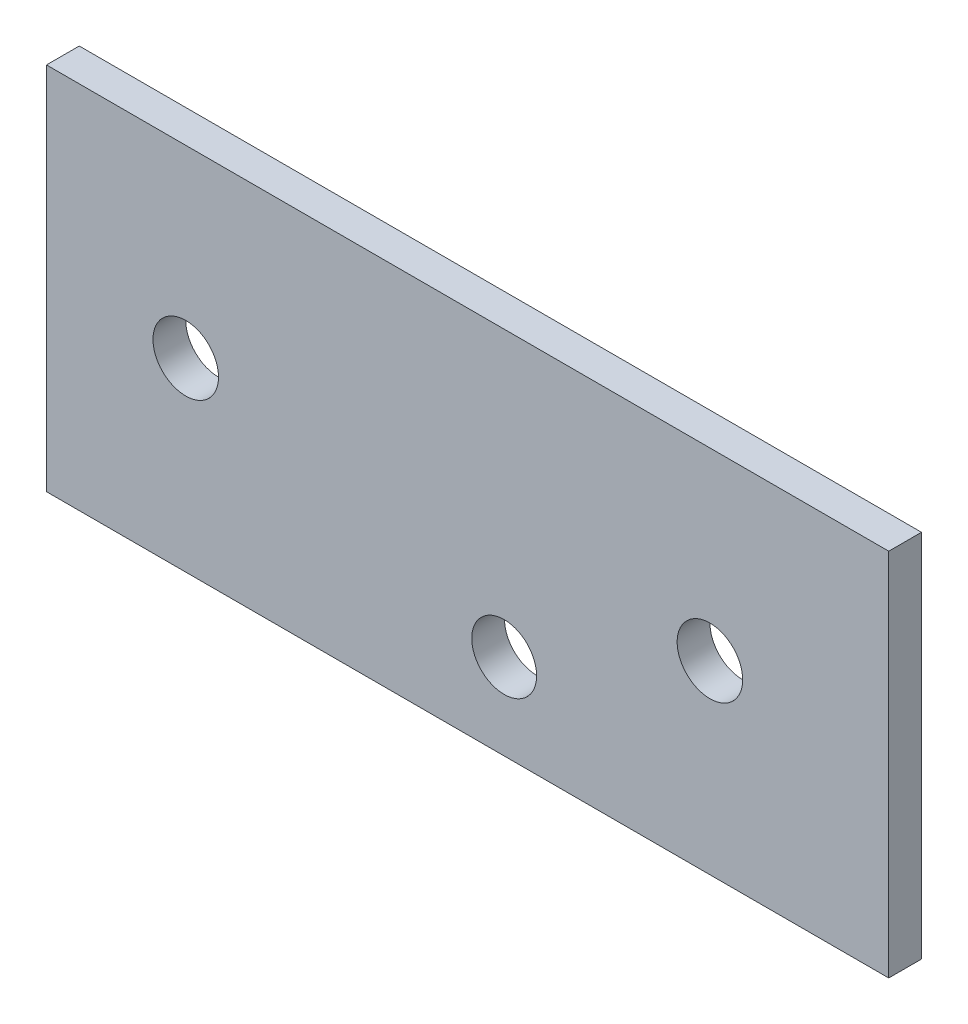
SolidWorks part; units mm, degrees
ref_plane "Front Plane" through (0, 0, 0) normal (0, 0, 1) x (1, 0, 0)
ref_plane "Top Plane" through (0, 0, 0) normal (0, 1, 0) x (1, 0, 0)
ref_plane "Right Plane" through (0, 0, 0) normal (1, 0, 0) x (0, 0, -1)
sketch "Sketch1" plane through (0, 0, 0) normal (0, 0, 1) x (1, 0, 0)
  line L1 (-38.8941, -159.024) -> (42.7306, -159.024)
  line L2 (-38.8941, -159.024) -> (-38.8941, -194.8462)
  line L3 (-38.8941, -194.8462) -> (42.7306, -194.8462)
  line L4 (42.7306, -159.024) -> (42.7306, -194.8462)
  circle A0 centre (-25.4, -176.8929) radius 3.175
  circle A1 centre (25.4, -176.8929) radius 3.175
  circle A2 centre (5.461, -186.5397) radius 3.1436
  circle A3 centre (5.461, -186.5397) radius 3.175 construction
  point P14 (0, 0)
extrude "Boss-Extrude1" add sketch "Sketch1" along normal blind 3.175
